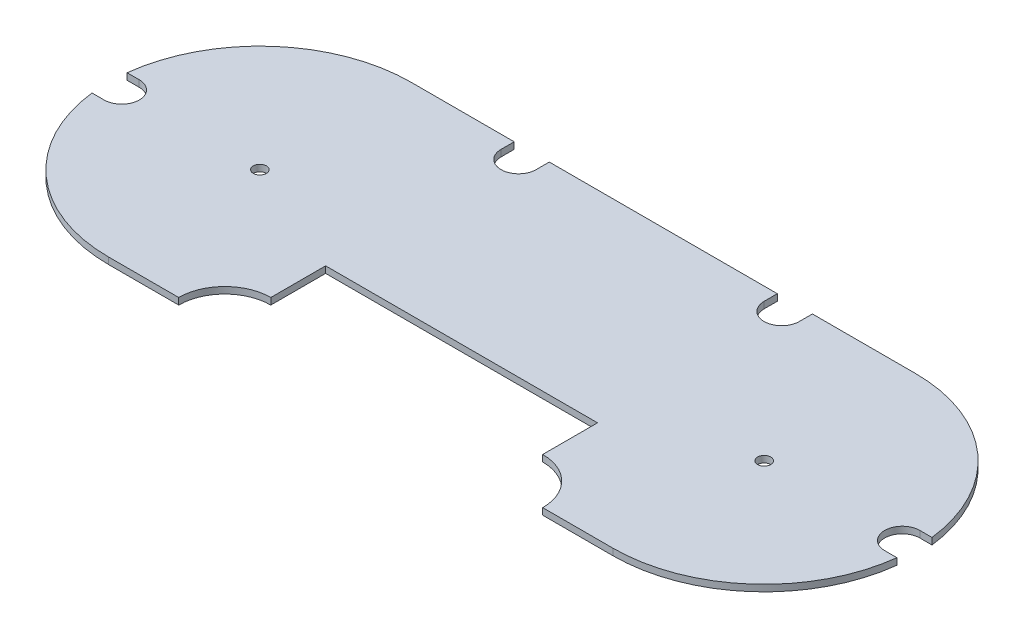
SolidWorks part; units mm, degrees
ref_plane "Front Plane" through (0, 0, 0) normal (0, 0, 1) x (1, 0, 0)
ref_plane "Top Plane" through (0, 0, 0) normal (0, 1, 0) x (1, 0, 0)
ref_plane "Right Plane" through (0, 0, 0) normal (1, 0, 0) x (0, 0, -1)
sketch "Sketch1" plane through (0, 0, 0) normal (0, 1, 0) x (1, 0, 0)
  line L0 (0, 0) -> (0, 34.5) construction
  line L1 (0, 34.5) -> (-26, 34.5)
  line L2 (0, 34.5) -> (26, 34.5)
  line L3 (-57.5, 34.5) -> (-57.5, -34.5) construction
  line L4 (57.5, 34.5) -> (57.5, -34.5) construction
  line L5 (-57.5, -34.5) -> (-41.5, -34.5)
  line L6 (0, 0) -> (0, -11.5) construction
  line L7 (-57.5, 0) -> (-89, 0) construction
  line L8 (57.5, 0) -> (89, 0) construction
  line L9 (-57.5, 0) -> (0, 0) construction
  line L10 (0, 0) -> (57.5, 0) construction
  line L11 (-31, -24) -> (-31, -11.5)
  line L12 (-31, -11.5) -> (31, -11.5)
  line L13 (31, -11.5) -> (31, -24)
  line L14 (41.5, -34.5) -> (57.5, -34.5)
  line L15 (-41.5, -34.5) -> (-41.5, -35.5) construction
  line L16 (-31, -24) -> (31, -24) construction
  line L17 (41.5, -34.5) -> (41.5, -35.5) construction
  line L20 (-34, 34.5) -> (-57.5, 34.5)
  line L21 (34, 34.5) -> (57.5, 34.5)
  line L22 (-26, 34.5) -> (-30, 34.5) construction
  line L23 (-30, 34.5) -> (-34, 34.5) construction
  line L24 (30, 31.5) -> (30, 34.5) construction
  line L25 (-30, 31.5) -> (-30, 34.5) construction
  line L26 (26, 34.5) -> (30, 34.5) construction
  line L27 (30, 34.5) -> (34, 34.5) construction
  line L28 (-91.7673, 4) -> (-91.7673, -4) construction
  line L29 (89, 0) -> (92, 0) construction
  line L30 (-89, 0) -> (-92, 0) construction
  line L31 (91.7673, 4) -> (89, 4)
  line L32 (91.7673, -4) -> (89, -4)
  line L33 (-91.7673, 4) -> (-89, 4)
  line L34 (-91.7673, -4) -> (-89, -4)
  line L35 (26, 34.5) -> (26, 31.5)
  line L36 (34, 34.5) -> (34, 31.5)
  line L37 (-34, 34.5) -> (-34, 31.5)
  line L38 (-26, 31.5) -> (-26, 34.5)
  arc A0 (-57.5, 34.5) -> (-91.7673, 4) centre (-57.5, 0) ccw
  arc A1 (57.5, 34.5) -> (91.7673, 4) centre (57.5, 0) cw
  arc A2 (-41.5, -34.5) -> (-31, -24) centre (-31, -34.5) cw
  arc A3 (31, -24) -> (41.5, -34.5) centre (31, -34.5) cw
  arc A8 (-91.7673, -4) -> (-57.5, -34.5) centre (-57.5, 0) ccw
  arc A9 (91.7673, -4) -> (57.5, -34.5) centre (57.5, 0) cw
  arc A10 (-91.7673, 4) -> (-91.7673, -4) centre (-57.5, 0) ccw construction
  arc A11 (91.7673, 4) -> (91.7673, -4) centre (57.5, 0) cw construction
  circle A12 centre (-57.5, 0) radius 1.5
  circle A13 centre (57.5, 0) radius 1.5
  arc A14 (-89, 4) -> (-89, -4) centre (-89, 0) cw
  arc A15 (89, 4) -> (89, -4) centre (89, 0) ccw
  arc A16 (-26, 31.5) -> (-34, 31.5) centre (-30, 31.5) cw
  arc A17 (34, 31.5) -> (26, 31.5) centre (30, 31.5) cw
  point P14 (0, -11.5)
  dimension "D5" = 10.5
  dimension "D8" = 3
  dimension "D9" = 3
  dimension "D11" = 4
  dimension "D12" = 60
  dimension "D1" = 69
  dimension "D2" = 184
  dimension "D3" = 23
  dimension "D4" = 62
  dimension "D6" = 1
  dimension "D7" = 1
  dimension "D10" = 30
extrude "board" add sketch "Sketch1" along normal blind 1.5
